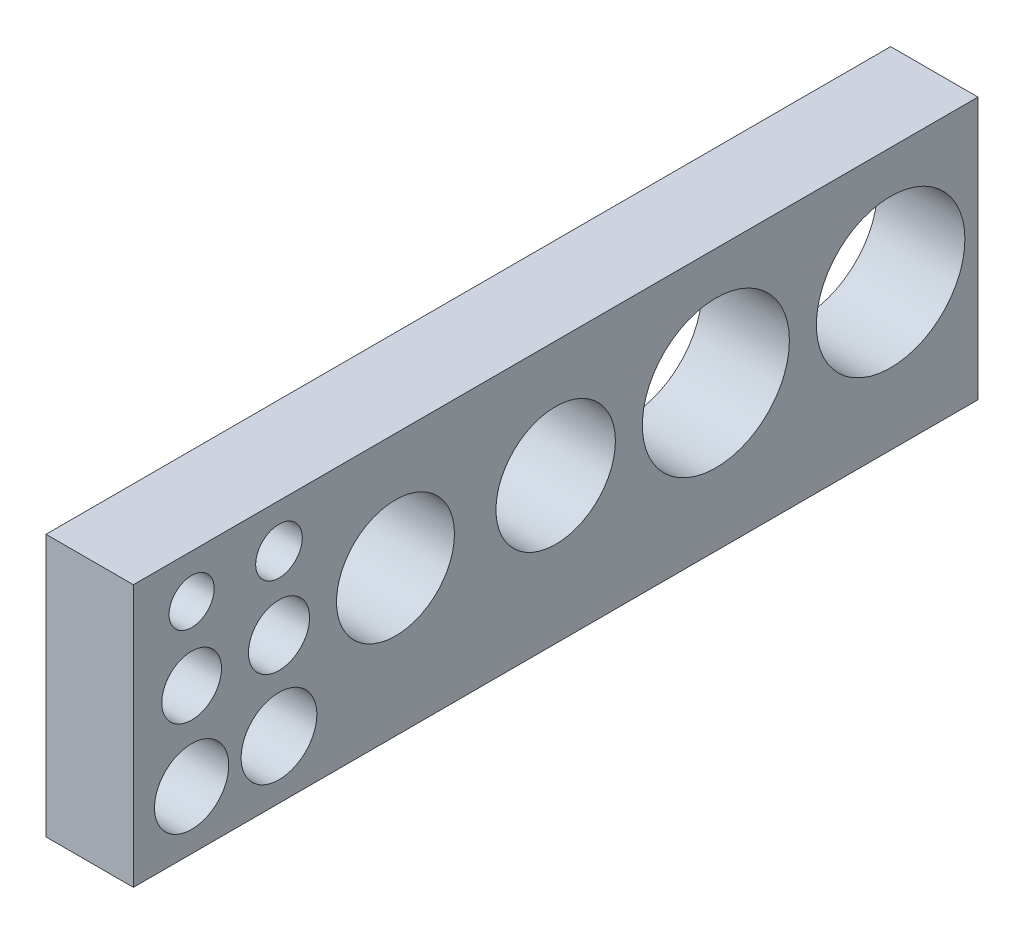
SolidWorks part; units mm, degrees
ref_plane "前视基准面" through (0, 0, 0) normal (0, 0, 1) x (1, 0, 0)
ref_plane "上视基准面" through (0, 0, 0) normal (0, 1, 0) x (1, 0, 0)
ref_plane "右视基准面" through (0, 0, 0) normal (1, 0, 0) x (0, 0, -1)
other "Configuration Table"
sketch "草图1" plane through (0, 0, 0) normal (1, 0, 0) x (0, 0, -1)
  line L0 (0, 0) -> (138.0498, 0) construction
  line L1 (-5.7164, 5) -> (15.659, 5) construction
  line L2 (0, 0) -> (0, 17.7644) construction
  line L3 (6, 5) -> (6, -7.7773) construction
  line L4 (-3.5389, -6) -> (14.6873, -6) construction
  line L6 (-4, 8) -> (54, 8)
  line L7 (-4, 8) -> (-4, -10)
  line L8 (-4, -10) -> (54, -10)
  line L9 (54, 8) -> (54, -10)
  circle A0 centre (0, 0) radius 2.05
  circle A1 centre (6, 0) radius 2.1
  circle A2 centre (0, 5) radius 1.55
  circle A3 centre (6, 5) radius 1.6
  circle A4 centre (0, -6) radius 2.55
  circle A5 centre (6, -6) radius 2.6
  circle A6 centre (14, 0) radius 4.05
  circle A7 centre (25, 0) radius 4.1
  circle A8 centre (36, 0) radius 5.05
  circle A9 centre (48, 0) radius 5.1
  point P32 (0, 0)
  point P35 (0.6111, -10.3902)
  dimension "D2" = 4.1
  dimension "D3" = 4.2
  dimension "D4" = 3.1
  dimension "D5" = 3.2
  dimension "D9" = 8.1
  dimension "D10" = 8.2
  dimension "D11" = 10.1
  dimension "D12" = 10.2
  dimension "D17" = 5.1
  dimension "D18" = 5.2
  dimension "D19" = 4
  dimension "D1" = 0
  dimension "D6" = 5
  dimension "D7" = 6
  dimension "D8" = 6
  dimension "D13" = 8
  dimension "D14" = 11
  dimension "D15" = 11
  dimension "D16" = 12
  dimension "D20" = 4
  dimension "D21" = 3
  dimension "D22" = 6
extrude "凸台-拉伸1" add sketch "草图1" along normal blind 6
